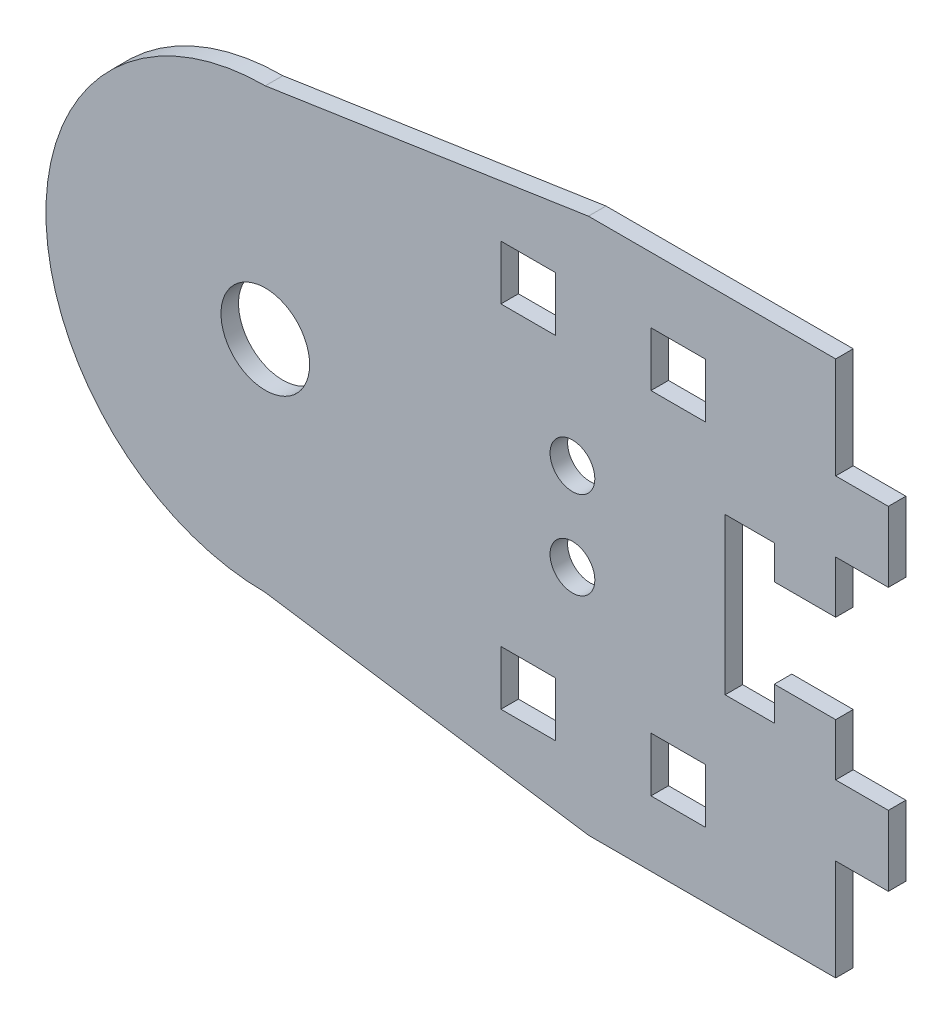
SolidWorks part; units mm, degrees
ref_plane "前视基准面" through (0, 0, 0) normal (0, 0, 1) x (1, 0, 0)
ref_plane "上视基准面" through (0, 0, 0) normal (0, 1, 0) x (1, 0, 0)
ref_plane "右视基准面" through (0, 0, 0) normal (1, 0, 0) x (0, 0, -1)
sketch "草图1" plane through (0, 0, 0) normal (0, 0, 1) x (1, 0, 0)
  line L0 (0, 0) -> (118.4069, 0) construction
  line L8 (38.5, -5) -> (38.5, -19.6678) construction
  line L9 (43.95, -16.9) -> (43.95, -23.1)
  line L10 (26.85, -16.9) -> (33.05, -16.9)
  line L11 (26.85, -16.9) -> (26.85, -23.1)
  line L12 (26.85, -23.1) -> (33.05, -23.1)
  line L13 (33.05, -16.9) -> (33.05, -23.1)
  line L14 (26.85, -16.9) -> (33.05, -23.1) construction
  line L15 (26.85, -23.1) -> (33.05, -16.9) construction
  line L16 (50.15, -23.1) -> (43.95, -23.1)
  line L17 (50.15, -16.9) -> (50.15, -23.1)
  line L18 (50.15, -16.9) -> (43.95, -16.9)
  line L19 (33.05, 16.9) -> (33.05, 23.1)
  line L20 (26.85, 23.1) -> (33.05, 23.1)
  line L21 (26.85, 16.9) -> (33.05, 16.9)
  line L22 (26.85, 16.9) -> (26.85, 23.1)
  line L23 (43.95, 16.9) -> (43.95, 23.1)
  line L24 (50.15, 23.1) -> (43.95, 23.1)
  line L25 (50.15, 16.9) -> (50.15, 23.1)
  line L26 (50.15, 16.9) -> (43.95, 16.9)
  line L27 (0, -25) -> (36.8229, -30.548)
  line L30 (0, 25) -> (36.8229, 30.548)
  line L32 (35, -5) -> (35, 5) construction
  line L33 (58, 5.05) -> (58, 8.9)
  line L40 (36.8229, 30.548) -> (65, 30.548)
  line L41 (65, -30.548) -> (36.8229, -30.548)
  line L54 (65, 5.05) -> (58, 5.05)
  line L55 (58, 8.9) -> (52.4, 8.9)
  line L56 (52.4, 8.9) -> (52.4, 5.15)
  line L59 (65, 30.548) -> (65, 5.05) construction
  line L60 (65, 19) -> (71, 19)
  line L61 (71, 19) -> (71, 11)
  line L62 (71, 11) -> (65, 11)
  line L63 (71, 15) -> (65, 15) construction
  line L64 (65, 11) -> (65, 5.05)
  line L65 (65, 19) -> (65, 30.548)
  line L67 (52.4, -8.9) -> (52.4, -5.15)
  line L68 (58, -8.9) -> (52.4, -8.9)
  line L69 (65, -5.05) -> (58, -5.05)
  line L70 (58, -5.05) -> (58, -8.9)
  line L71 (71, -15) -> (65, -15) construction
  line L72 (65, -11) -> (65, -5.05)
  line L73 (71, -11) -> (65, -11)
  line L74 (71, -19) -> (71, -11)
  line L75 (65, -19) -> (71, -19)
  line L76 (65, -19) -> (65, -30.548)
  line L77 (52.4, -5.15) -> (52.4, 5.15)
  circle A0 centre (0, 0) radius 5.05
  circle A1 centre (35, 5) radius 2.55
  circle A5 centre (35, -5) radius 2.55
  circle A6 centre (0, 0) radius 25 construction
  arc A7 (0, 25) -> (0, -25) centre (0, 0) ccw
  circle A8 centre (0, 0) radius 40 construction
  point P10 (29.95, -20)
  point P22 (47.05, -20)
  point P31 (47.05, 20)
  point P52 (42, 0)
  point P63 (65, -8.025)
  dimension "D1" = 10.1
  dimension "D5" = 30
  dimension "D6" = 6.2
  dimension "D9" = 80
  dimension "D10" = 8.9
  dimension "D11" = 5.05
  dimension "D17" = 5.1
  dimension "D2" = 5
  dimension "D3" = 3.5
  dimension "D4" = 6.2
  dimension "D7" = 17.1
  dimension "D8" = 5.6
  dimension "D12" = 7
  dimension "D13" = 65
  dimension "D14" = 15
  dimension "D15" = 8
  dimension "D16" = 6
extrude "凸台-拉伸1" add sketch "草图1" along normal blind 2
sketch "草图2" plane through (65, 0, 0) normal (1, 0, 0) x (0, 0, -1)
  line L0 (-1, -5.05) -> (-1, 5.05) construction
  line L1 (-2, -5.05) -> (0, -5.05) construction
  line L2 (-2, 5.05) -> (0, 5.05) construction
  circle A0 centre (-1, 0) radius 5.05
